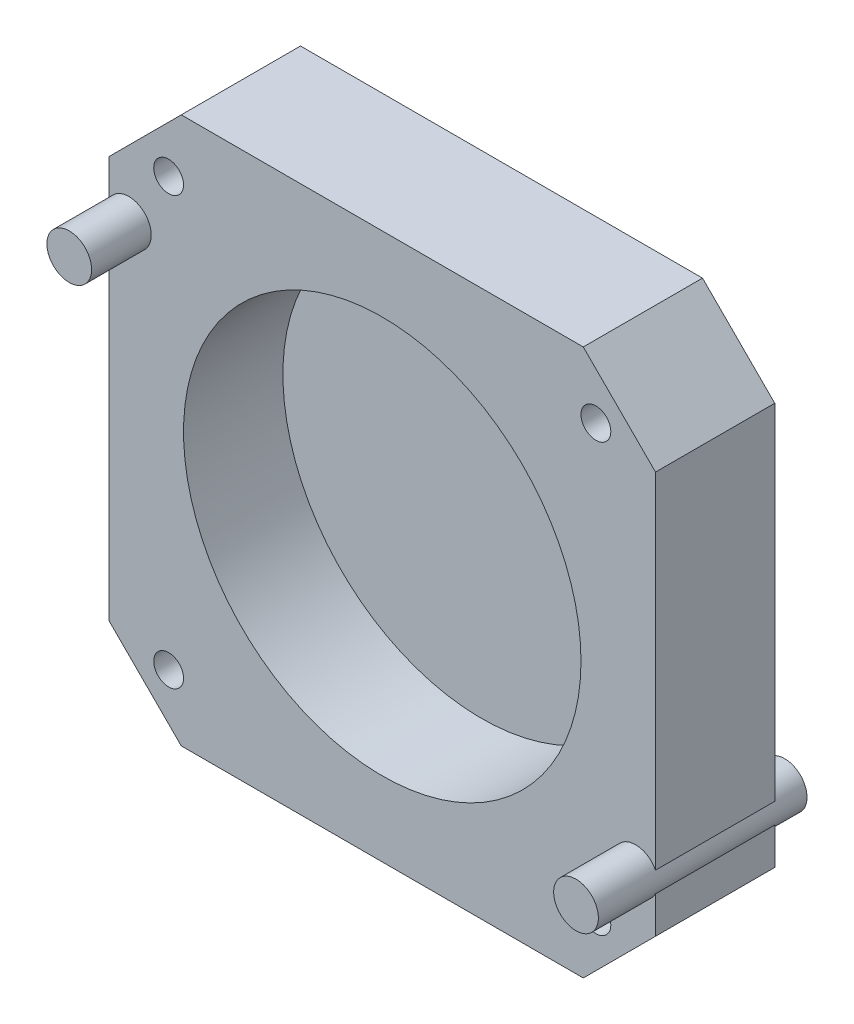
SolidWorks part; units mm, degrees
ref_plane "前视基准面" through (0, 0, 0) normal (0, 0, 1) x (1, 0, 0)
ref_plane "上视基准面" through (0, 0, 0) normal (0, 1, 0) x (1, 0, 0)
ref_plane "右视基准面" through (0, 0, 0) normal (1, 0, 0) x (0, 0, -1)
sketch "草图1" plane through (0, 0, 0) normal (0, 0, 1) x (1, 0, 0)
  line L1 (-27.5, 27.5) -> (27.5, 27.5)
  line L2 (-27.5, 27.5) -> (-27.5, -27.5)
  line L3 (-27.5, -27.5) -> (27.5, -27.5)
  line L4 (27.5, 27.5) -> (27.5, -27.5)
  line L5 (-27.5, 27.5) -> (27.5, -27.5) construction
  line L6 (-27.5, -27.5) -> (27.5, 27.5) construction
  point P0 (0, 0)
  dimension "D1" = 55
  dimension "D2" = 55
extrude "凸台-拉伸1" add sketch "草图1" along normal blind 12
sketch "草图2" plane through (0, 0, 12) normal (0, 0, 1) x (1, 0, 0)
  line L0 (0, 27.5) -> (0, 0) construction
  line L1 (27.5, 27.5) -> (-27.5, 27.5) construction
  line L2 (0, 0) -> (27.5, 0) construction
  line L3 (27.5, -27.5) -> (27.5, 27.5) construction
  circle A0 centre (21.5, 21.5) radius 1.5
  circle A1 centre (21.5, -21.5) radius 1.5
  circle A2 centre (-21.5, -21.5) radius 1.5
  circle A3 centre (-21.5, 21.5) radius 1.5
  dimension "D1" = 43
  dimension "D2" = 43
  dimension "D3" = 3
extrude "切除-拉伸1" cut sketch "草图2" against normal up to next
sketch "草图3" plane through (0, 0, 12) normal (0, 0, 1) x (1, 0, 0)
  circle A0 centre (0, 0) radius 20
  dimension "D1" = 40
extrude "切除-拉伸2" cut sketch "草图3" against normal blind 10
sketch "草图4" plane through (0, 0, 12) normal (0, 0, 1) x (1, 0, 0)
  line L0 (-27.5, 27.5) -> (0, 0) construction
  line L1 (0, 0) -> (27.5, 27.5) construction
  line L2 (-27.5, 20.2297) -> (-20.2297, 27.5)
  line L3 (-27.5, 27.5) -> (-27.5, -27.5) construction
  line L4 (27.5, 27.5) -> (-27.5, 27.5) construction
  line L5 (20.2297, -27.5) -> (27.5, -20.2297)
  line L6 (20.2297, 27.5) -> (27.5, 20.2297)
  line L7 (27.5, -27.5) -> (27.5, 27.5) construction
  line L8 (27.5, 20.2297) -> (27.5, 27.5)
  line L9 (27.5, 27.5) -> (20.2297, 27.5)
  line L10 (-20.2297, -27.5) -> (-27.5, -27.5)
  line L11 (-27.5, -20.2297) -> (-20.2297, -27.5)
  line L12 (-27.5, -27.5) -> (-27.5, -20.2297)
  line L13 (-27.5, 20.2297) -> (-27.5, 27.5)
  line L14 (-27.5, 27.5) -> (-20.2297, 27.5)
  line L15 (20.2297, -27.5) -> (27.5, -27.5)
  line L16 (27.5, -27.5) -> (27.5, -20.2297)
  dimension "D1" = 67.5
  dimension "D2" = 67.5
extrude "切除-拉伸3" cut sketch "草图4" against normal up to next
sketch "草图5" plane through (0, 0, 12) normal (0, 0, 1) x (1, 0, 0)
  line L0 (20.2297, 27.5) -> (-20.2297, 27.5) construction
  line L1 (-27.5, 20.2297) -> (-27.5, -20.2297) construction
  line L2 (-20.2297, -27.5) -> (20.2297, -27.5) construction
  line L3 (27.5, -20.2297) -> (27.5, 20.2297) construction
  circle A0 centre (-25.5, 15.5) radius 2.25
  circle A1 centre (25.5, -15.5) radius 2.25
  point P10 (0, 0)
  dimension "D1" = 12
  dimension "D2" = 2
  dimension "D3" = 4.5
  dimension "D5" = 12
  dimension "D6" = 2
  dimension "D4" = 2
extrude "凸台-拉伸2" add sketch "草图5" along normal blind 6 and the other way blind 15
sketch "草图6" plane through (0, 0, 0) normal (0, 0, -1) x (-1, 0, 0)
  line L1 (-7, 7) -> (7, 7)
  line L2 (-7, 7) -> (-7, -7)
  line L3 (-7, -7) -> (7, -7)
  line L4 (7, 7) -> (7, -7)
  line L5 (-7, 7) -> (7, -7) construction
  line L6 (-7, -7) -> (7, 7) construction
  point P0 (0, 0)
  dimension "D1" = 14
  dimension "D2" = 14
extrude "凸台-拉伸3" add sketch "草图6" along normal blind 1
sketch "草图7" plane through (0, 0, -1) normal (0, 0, -1) x (-1, 0, 0)
  circle A0 centre (0, 0) radius 3.5
  dimension "D1" = 7
extrude "凸台-拉伸4" add sketch "草图7" along normal blind 0.5
sketch "草图8" plane through (0, 0, 0) normal (0, 0, -1) x (-1, 0, 0)
  line L1 (-15, 15) -> (15, 15)
  line L2 (-15, 15) -> (-15, -15)
  line L3 (-15, -15) -> (15, -15)
  line L4 (15, 15) -> (15, -15)
  line L5 (-15, 15) -> (15, -15) construction
  line L6 (-15, -15) -> (15, 15) construction
  point P0 (0, 0)
  dimension "D1" = 30
  dimension "D2" = 30
extrude "凸台-拉伸5" add sketch "草图8" along normal blind 0.1
